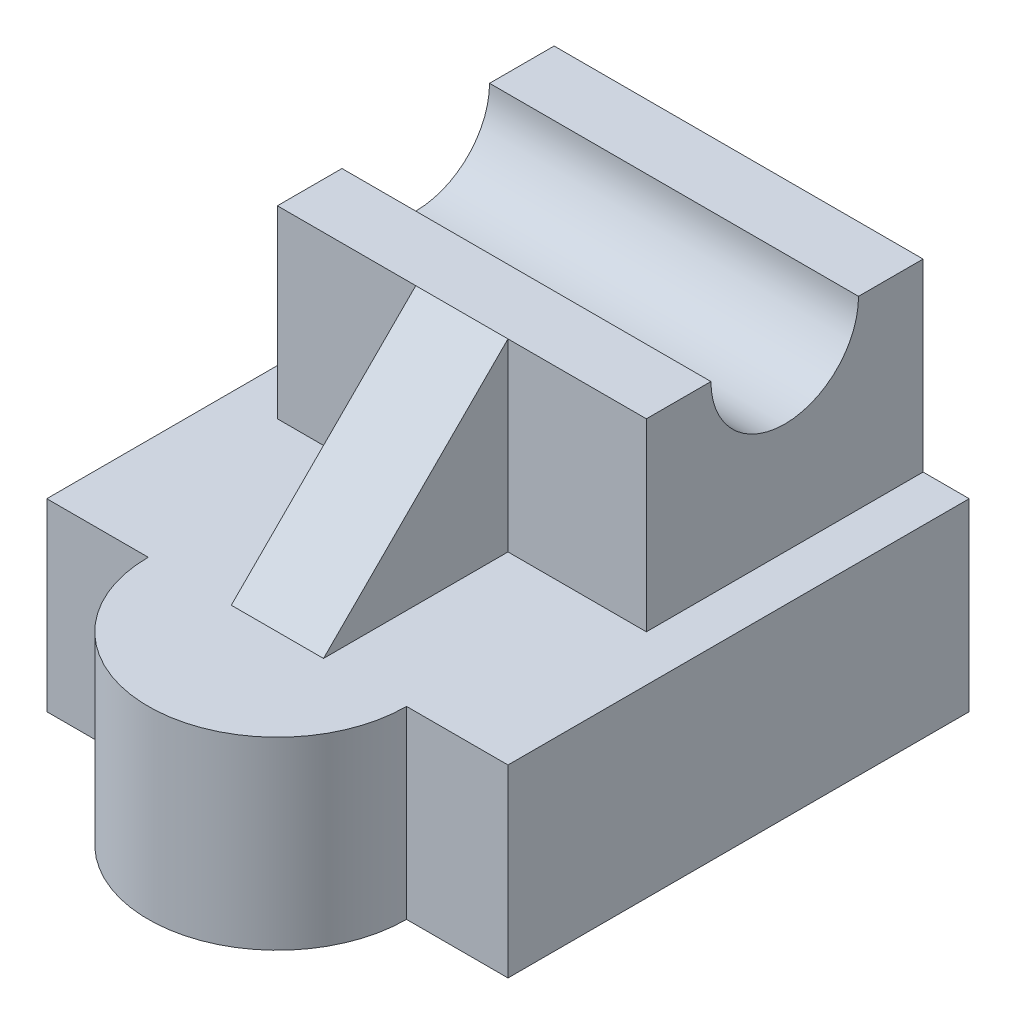
SolidWorks part; units mm, degrees
material "Plain Carbon Steel"
ref_plane "Front Plane" through (0, 0, 0) normal (0, 0, 1) x (1, 0, 0)
ref_plane "Top Plane" through (0, 0, 0) normal (0, 1, 0) x (1, 0, 0)
ref_plane "Right Plane" through (0, 0, 0) normal (1, 0, 0) x (0, 0, -1)
sketch "Sketch1" plane through (0, 0, 0) normal (0, 0, 1) x (1, 0, 0)
  line L0 (-25, 0) -> (25, 0)
  line L1 (25, 0) -> (25, 20)
  line L2 (25, 20) -> (-25, 20)
  line L3 (-25, 20) -> (-25, 0)
  point P5 (0, 0)
  dimension "D1" = 50
  dimension "D2" = 20
extrude "Boss-Extrude1" add sketch "Sketch1" along normal blind 50
sketch "Sketch2" plane through (0, 20, 0) normal (0, 1, 0) x (1, 0, 0)
  line L0 (0, 0) -> (0, -50) construction
  line L1 (25, -50) -> (-25, -50) construction
  line L3 (-20, 0) -> (20, 0)
  line L4 (25, 0) -> (-25, 0) construction
  line L5 (20, 0) -> (20, -30)
  line L6 (20, -30) -> (-20, -30)
  line L7 (-20, -30) -> (-20, 0)
  dimension "D1" = 40
  dimension "D2" = 30
extrude "Boss-Extrude2" add sketch "Sketch2" along normal blind 20
sketch "Sketch3" plane through (20, 0, 0) normal (1, 0, 0) x (0, 0, -1)
  line L0 (-23, 40) -> (-7, 40)
  line L1 (-30, 40) -> (0, 40) construction
  arc A0 (-7, 40) -> (-23, 40) centre (-15, 40) cw
  dimension "D1" = 8
extrude "Cut-Extrude1" cut sketch "Sketch3" against normal through all
sketch "Sketch4" plane through (0, 20, 0) normal (0, 1, 0) x (1, 0, 0)
  line L0 (14, -50) -> (-14, -50)
  line L1 (25, -50) -> (-25, -50) construction
  arc A0 (-14, -50) -> (14, -50) centre (0, -50) ccw
  dimension "D1" = 14
extrude "Boss-Extrude3" add sketch "Sketch4" against normal blind 20
sketch "Sketch5" plane through (0, 0, 0) normal (1, 0, 0) x (0, 0, -1)
  line L0 (-30, 20) -> (-30, 40)
  line L1 (-50, 20) -> (0, 20) construction
  line L2 (-30, 40) -> (-50, 20)
  line L3 (-50, 20) -> (-30, 20)
extrude "Boss-Extrude4" add sketch "Sketch5" along normal mid plane 10
